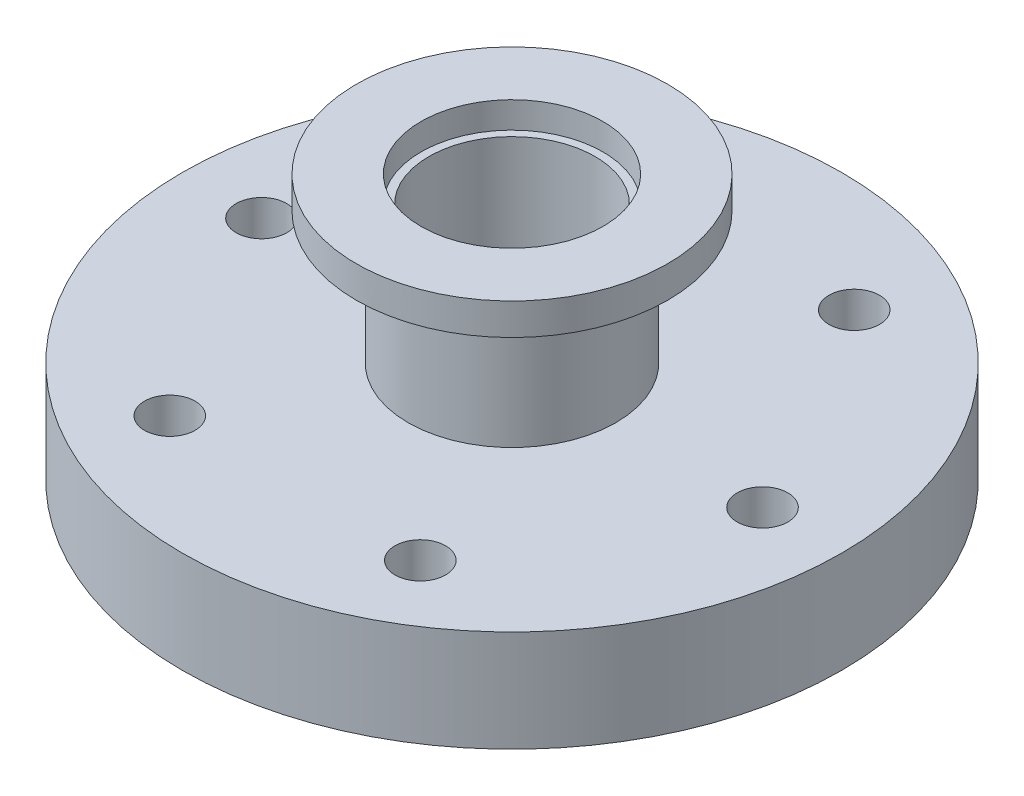
SolidWorks part; units mm, degrees
ref_plane "Front Plane" through (0, 0, 0) normal (0, 0, 1) x (1, 0, 0)
ref_plane "Top Plane" through (0, 0, 0) normal (0, 1, 0) x (1, 0, 0)
ref_plane "Right Plane" through (0, 0, 0) normal (1, 0, 0) x (0, 0, -1)
sketch "Sketch1" plane through (0, 0, 0) normal (0, 1, 0) x (1, 0, 0)
  circle A0 centre (0, 0) radius 31.75
  circle A1 centre (-24.125, 0) radius 2.413
  dimension "D1" = 63.5
  dimension "D3" = 4.826
  dimension "D2" = 24.125
extrude "Boss-Extrude1" add sketch "Sketch1" along normal blind 9.779 contours A0
sketch "Sketch2" plane through (0, 9.779, 0) normal (0, 1, 0) x (1, 0, 0)
  circle A0 centre (-24.125, 0) radius 2.4384
  dimension "D2" = 4.8768
  dimension "D1" = 24.125
extrude "Cut-Extrude1" cut sketch "Sketch2" against normal through all
pattern_circular "CirPattern1" count 6 over 360 about axis through (0, 0, 0) along (0, 1, 0) of "Cut-Extrude1"
sketch "Sketch3" plane through (0, 0, 0) normal (0, -1, 0) x (1, 0, 0)
  circle A0 centre (0, 0) radius 17.8435
  circle A1 centre (0, 0) radius 20.955
  dimension "D1" = 41.91
  dimension "D2" = 35.687
extrude "Cut-Extrude2" cut sketch "Sketch3" against normal blind 2
sketch "Sketch4" plane through (0, 9.779, 0) normal (0, 1, 0) x (1, 0, 0)
  circle A0 centre (0, 0) radius 8
  circle A1 centre (0, 0) radius 10
  dimension "D1" = 16
  dimension "D2" = 20
extrude "Boss-Extrude2" add sketch "Sketch4" along normal blind 12.7
sketch "Sketch5" plane through (0, 22.479, 0) normal (0, 1, 0) x (1, 0, 0)
  circle A0 centre (0, 0) radius 14.986
  dimension "D1" = 29.972
extrude "Boss-Extrude3" add sketch "Sketch5" along normal blind 3.048 contours A0
sketch "Sketch6" plane through (0, 25.527, 0) normal (0, 1, 0) x (1, 0, 0)
  circle A0 centre (0, 0) radius 8.763
  dimension "D1" = 17.526
extrude "Cut-Extrude3" cut sketch "Sketch6" against normal blind 2.54
sketch "Sketch7" plane through (0, 0, 0) normal (0, 0, 1) x (1, 0, 0)
  line L0 (-14.986, 22.479) -> (-10, 22.479)
  line L1 (-10, 22.479) -> (-10, 21.143)
  line L2 (-10, 21.143) -> (-14.986, 22.479)
  line L3 (0, 0) -> (0, 29.4706) construction
  dimension "D1" = 165
revolve "Revolve1" add sketch "Sketch7" angle 360 about L3
sketch "Sketch8" plane through (0, 22.987, 0) normal (0, 1, 0) x (1, 0, 0)
  circle A0 centre (0, 0) radius 8
  dimension "16" = 16
extrude "Cut-Extrude4" cut sketch "Sketch8" against normal through all
